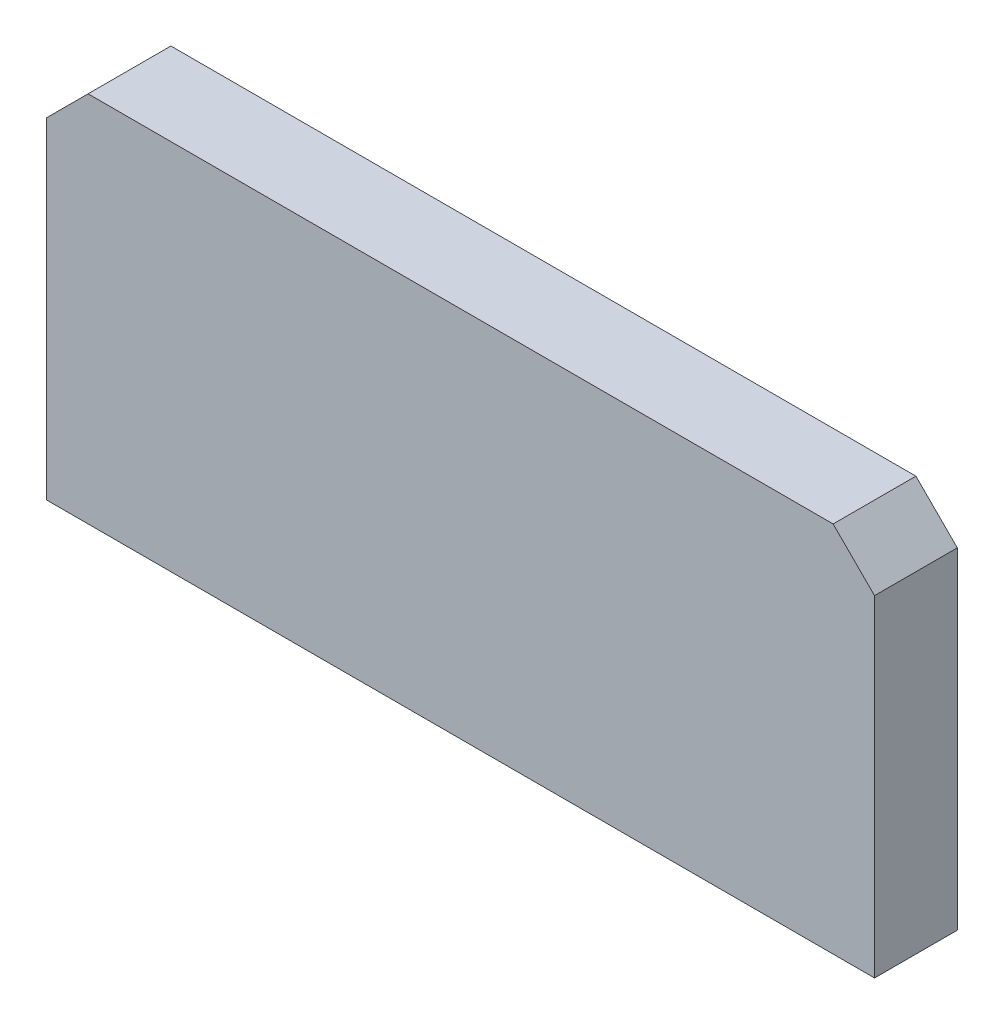
SolidWorks part; units mm, degrees
ref_plane "前视基准面" through (0, 0, 0) normal (0, 0, 1) x (1, 0, 0)
ref_plane "上视基准面" through (0, 0, 0) normal (0, 1, 0) x (1, 0, 0)
ref_plane "右视基准面" through (0, 0, 0) normal (1, 0, 0) x (0, 0, -1)
ref_plane "基准面4" through (0, 0, 0) normal (0, 0, -1) x (-1, 0, 0)
sketch "草图1" plane through (0, 0, 0) normal (0, 0, -1) x (-1, 0, 0)
  line L0 (50, -20) -> (50, 20)
  line L1 (50, 20) -> (45, 25)
  line L2 (45, 25) -> (-45, 25)
  line L3 (-45, 25) -> (-50, 20)
  line L4 (-50, 20) -> (-50, -20)
  line L5 (-50, -20) -> (50, -20)
extrude "凸台-拉伸1" add sketch "草图1" against normal blind 10
